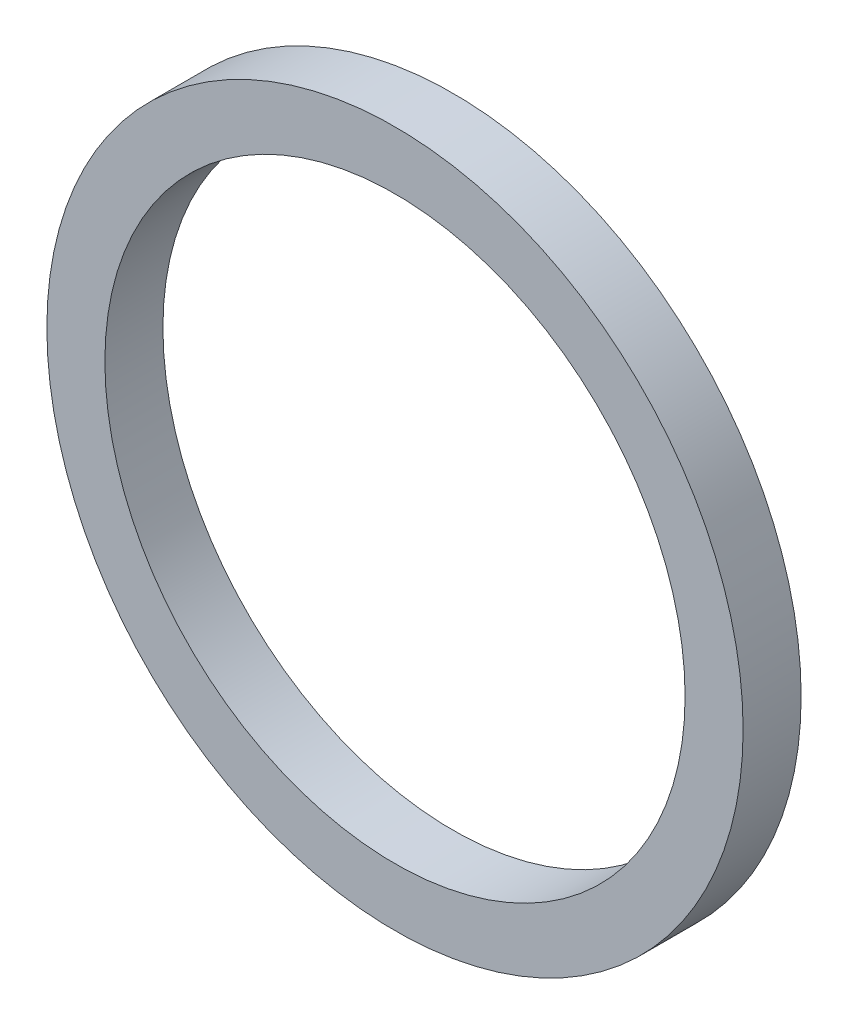
SolidWorks part; units mm, degrees
ref_plane "前视基准面" through (0, 0, 0) normal (0, 0, 1) x (1, 0, 0)
ref_plane "上视基准面" through (0, 0, 0) normal (0, 1, 0) x (1, 0, 0)
ref_plane "右视基准面" through (0, 0, 0) normal (1, 0, 0) x (0, 0, -1)
other "Configuration Table"
sketch "草图1" plane through (0, 0, 0) normal (0, 0, 1) x (1, 0, 0)
  circle A0 centre (0, 0) radius 5
  circle A1 centre (0, 0) radius 6
  dimension "D1" = 10
  dimension "D2" = 12
extrude "凸台-拉伸1" add sketch "草图1" along normal blind 1
